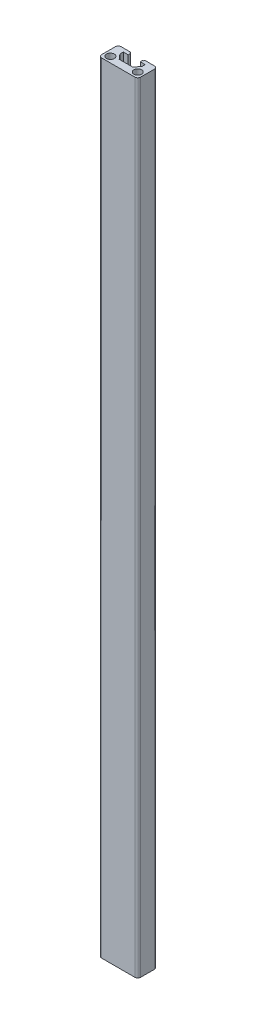
SolidWorks part; units mm, degrees
ref_plane "前视基准面" through (0, 0, 0) normal (0, 0, 1) x (1, 0, 0)
ref_plane "上视基准面" through (0, 0, 0) normal (0, 1, 0) x (1, 0, 0)
ref_plane "右视基准面" through (0, 0, 0) normal (1, 0, 0) x (0, 0, -1)
sketch "草图1" plane through (0, 0, 0) normal (0, 1, 0) x (1, 0, 0)
  line L0 (0, 0) -> (20, 0)
  line L1 (20, 0) -> (20, 10)
  line L2 (20, 10) -> (13.65, 10)
  line L3 (0, 10) -> (0, 0)
  line L4 (6.35, 10) -> (6.35, 9.5104)
  line L5 (6.35, 9.5104) -> (6.9, 9.5104)
  line L6 (6.9, 9.5104) -> (6.9, 8.2)
  line L7 (6.9, 8.2) -> (4.4, 8.2)
  line L8 (4.4, 8.2) -> (4.4, 6.4475)
  line L9 (4.4, 6.4475) -> (6.5873, 3.9)
  line L11 (15.6, 6.4475) -> (15.6, 8.2)
  line L12 (15.6, 8.2) -> (13.1, 8.2)
  line L13 (13.1, 8.2) -> (13.1, 9.5104)
  line L14 (13.1, 9.5104) -> (13.65, 9.5104)
  line L15 (13.65, 9.5104) -> (13.65, 10)
  line L16 (6.35, 10) -> (0, 10)
  line L17 (10, 0) -> (10, 13.7687) construction
  line L18 (6.5873, 3.9) -> (13.4127, 3.9)
  line L19 (13.4127, 3.9) -> (15.6, 6.4475)
  circle A0 centre (3, 3) radius 2
  circle A1 centre (17, 3) radius 2
  point P12 (10, 3.9)
  point P24 (0, 0)
  point P29 (4.3833, 0)
  dimension "D8" = 4
  dimension "D1" = 20
  dimension "D2" = 10
  dimension "D3" = 7.3
  dimension "D4" = 6.2
  dimension "D5" = 1.8
  dimension "D6" = 4.3
  dimension "D7" = 11.2
  dimension "D9" = 3
  dimension "D10" = 14
extrude "凸台-拉伸1" add sketch "草图1" along normal blind 400
fillet "圆角1" radius 1.5 4 edges at (0, 200, -10) (0, 200, 0) (20, 200, -10) (20, 200, 0)
